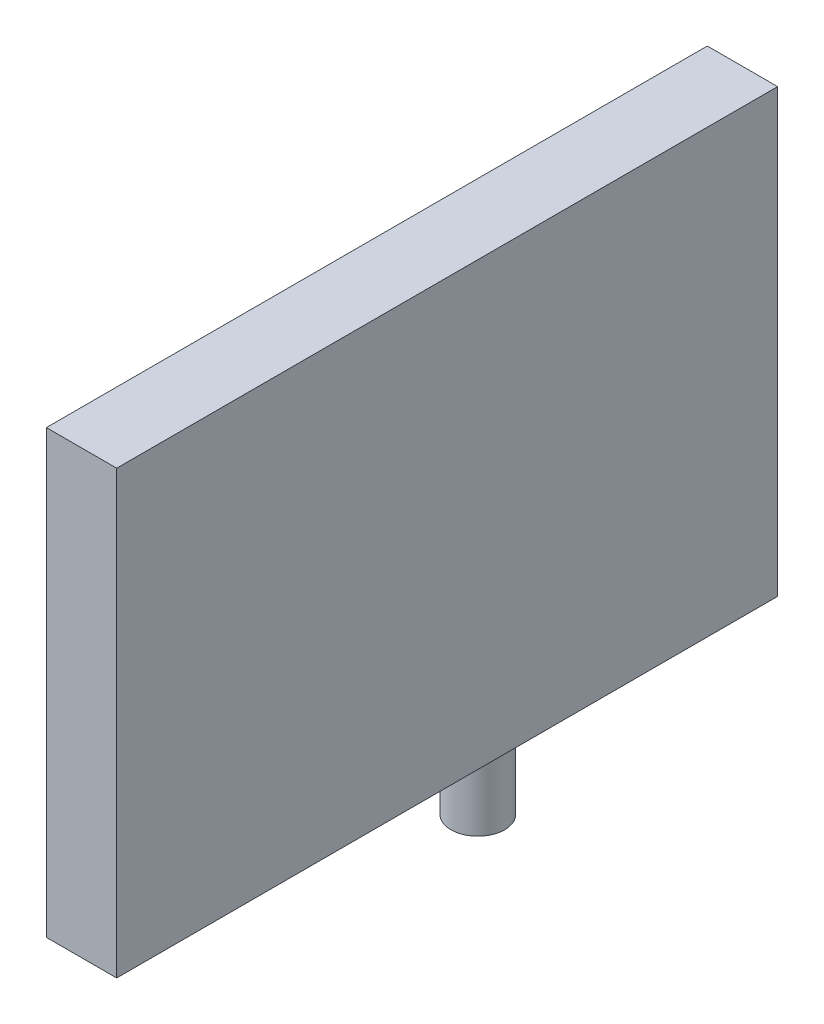
SolidWorks part; units mm, degrees
ref_plane "Front Plane" through (0, 0, 0) normal (0, 0, 1) x (1, 0, 0)
ref_plane "Top Plane" through (0, 0, 0) normal (0, 1, 0) x (1, 0, 0)
ref_plane "Right Plane" through (0, 0, 0) normal (1, 0, 0) x (0, 0, -1)
sketch "Sketch2" plane through (0, 0, 0) normal (1, 0, 0) x (0, 0, -1)
  line L1 (-46.998, 31.3958) -> (46.998, 31.3958)
  line L2 (-46.998, 31.3958) -> (-46.998, -31.3958)
  line L3 (-46.998, -31.3958) -> (46.998, -31.3958)
  line L4 (46.998, 31.3958) -> (46.998, -31.3958)
  line L5 (-46.998, 31.3958) -> (46.998, -31.3958) construction
  line L6 (-46.998, -31.3958) -> (46.998, 31.3958) construction
  point P0 (0, 0)
extrude "Boss-Extrude1" add sketch "Sketch2" along normal blind 10
sketch "Sketch3" plane through (0, -31.3958, 0) normal (0, -1, 0) x (-1, 0, 0)
  circle A0 centre (-5.5271, 8.8342) radius 3.8118
extrude "Boss-Extrude2" add sketch "Sketch3" along normal blind 10
